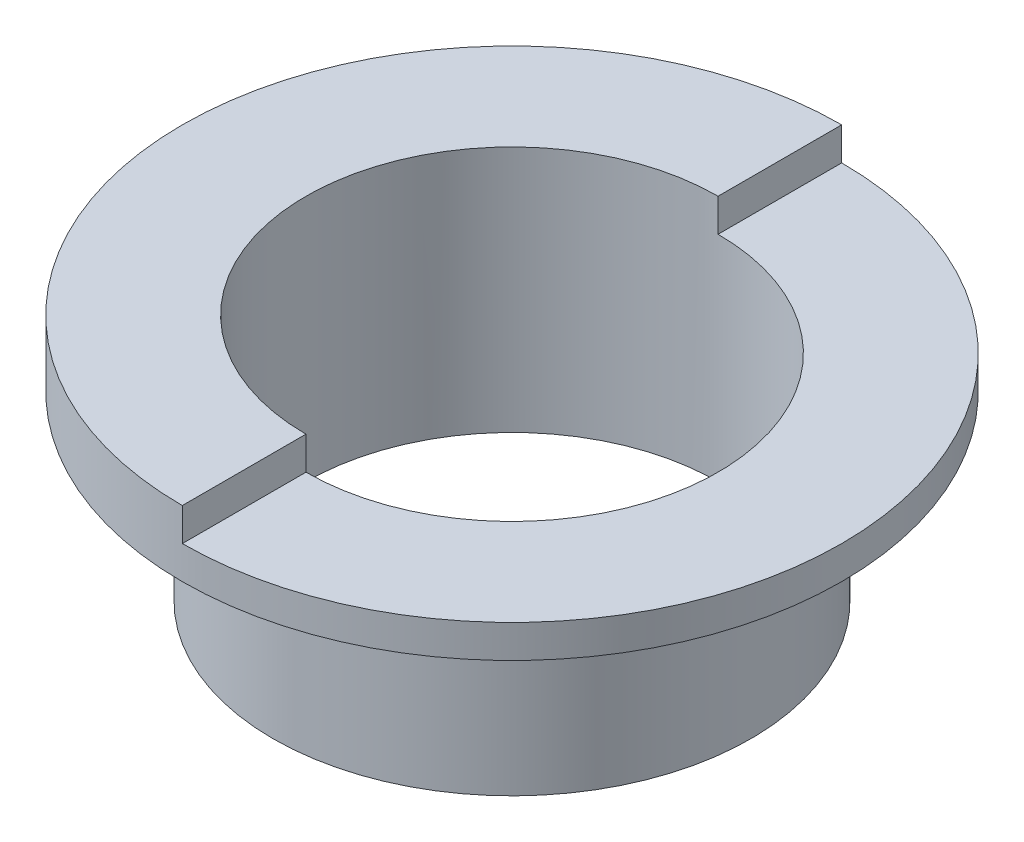
SolidWorks part; units mm, degrees
ref_plane "前基準面" through (0, 0, 0) normal (0, 0, 1) x (1, 0, 0)
ref_plane "上基準面" through (0, 0, 0) normal (0, 1, 0) x (1, 0, 0)
ref_plane "右基準面" through (0, 0, 0) normal (1, 0, 0) x (0, 0, -1)
sketch "草圖2" plane through (0, 0, 0) normal (0, 1, 0) x (1, 0, 0)
  circle A0 centre (0, 0) radius 12.5
  circle A1 centre (0, 0) radius 14.5
  dimension "D1" = 25
  dimension "D2" = 29
extrude "填料-伸長1" add sketch "草圖2" along normal blind 11
sketch "草圖3" plane through (0, 11, 0) normal (0, 1, 0) x (1, 0, 0)
  circle A0 centre (0, 0) radius 12.5
  circle A1 centre (0, 0) radius 20
  dimension "D1" = 25
  dimension "D2" = 40
extrude "填料-伸長2" add sketch "草圖3" along normal blind 2
sketch "草圖4" plane through (0, 13, 0) normal (0, 1, 0) x (1, 0, 0)
  line L0 (0, 20) -> (0, 12.5)
  line L1 (0, -12.5) -> (0, -20)
  arc A0 (0, 20) -> (0, -20) centre (0, 0) ccw
  arc A1 (0, 12.5) -> (0, -12.5) centre (0, 0) ccw
  circle A2 centre (0, 0) radius 20 construction
  circle A3 centre (0, 0) radius 12.5 construction
extrude "填料-伸長3" add sketch "草圖4" along normal blind 2
